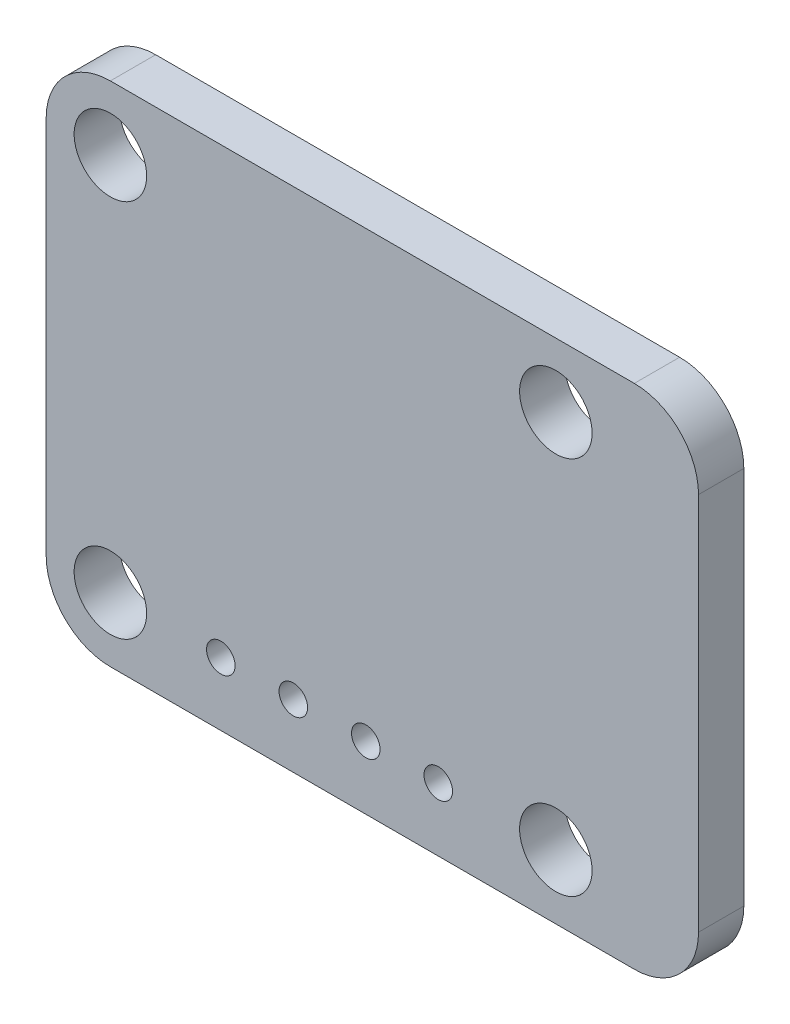
SolidWorks part; units mm, degrees
ref_plane "Plane1" through (0, 0, 0) normal (0, 0, 1) x (1, 0, 0)
ref_plane "Plane2" through (0, 0, 0) normal (0, 1, 0) x (1, 0, 0)
ref_plane "Plane3" through (0, 0, 0) normal (1, 0, 0) x (0, 0, -1)
sketch "Sketch1" plane through (0, 0, 0) normal (0, 0, 1) x (1, 0, 0)
  line L1 (9.18, -8.89) -> (-9.18, -8.89)
  line L2 (11.43, -6.64) -> (11.43, 6.64)
  line L3 (9.18, 8.89) -> (-9.18, 8.89)
  line L4 (-11.43, -6.64) -> (-11.43, 6.64)
  line L5 (11.43, -8.89) -> (-11.43, 8.89) construction
  line L6 (11.43, 8.89) -> (-11.43, -8.89) construction
  arc A0 (-9.18, -8.89) -> (-11.43, -6.64) centre (-9.18, -6.64) cw
  arc A1 (9.18, -8.89) -> (11.43, -6.64) centre (9.18, -6.64) ccw
  arc A2 (11.43, 6.64) -> (9.18, 8.89) centre (9.18, 6.64) ccw
  arc A3 (-9.18, 8.89) -> (-11.43, 6.64) centre (-9.18, 6.64) ccw
  point P0 (0, 0)
  dimension "D3" = 2.25
  dimension "D1" = 22.86
  dimension "D2" = 17.78
extrude "Boss-Extrude1" add sketch "Sketch1" along normal blind 1.5875
sketch "Sketch2" plane through (0, 0, 1.5875) normal (0, 0, 1) x (1, 0, 0)
  line L0 (6.43, -6.64) -> (-9.18, -6.64) construction
  line L1 (-9.18, -6.64) -> (-9.18, 6.64) construction
  line L2 (-9.18, 6.64) -> (6.43, 6.64) construction
  line L3 (6.43, 6.64) -> (6.43, -6.64) construction
  line L4 (11.43, -6.64) -> (11.43, 6.64) construction
  circle A0 centre (-9.18, 6.64) radius 1.27
  circle A1 centre (6.43, 6.64) radius 1.27
  circle A2 centre (6.43, -6.64) radius 1.27
  circle A3 centre (-9.18, -6.64) radius 1.27
  circle A4 centre (-5.3096, -6.6752) radius 0.5
  circle A5 centre (-2.7696, -6.6752) radius 0.5
  circle A6 centre (-0.2296, -6.6752) radius 0.5
  circle A7 centre (2.3104, -6.6752) radius 0.5
  arc A8 (-9.18, 8.89) -> (-11.43, 6.64) centre (-9.18, 6.64) ccw construction
  arc A9 (-11.43, -6.64) -> (-9.18, -8.89) centre (-9.18, -6.64) ccw construction
  dimension "D1" = 2.54
  dimension "D2" = 1
  dimension "D4" = 5
  dimension "D3" = 4
extrude "Cut-Extrude1" cut sketch "Sketch2" against normal through all
